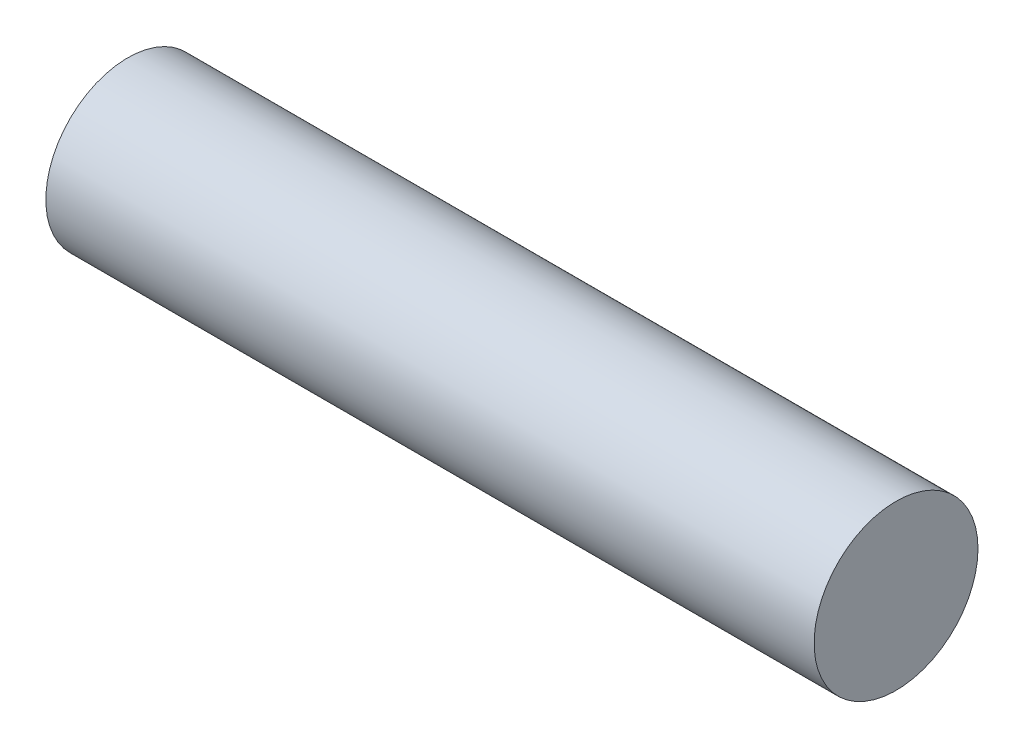
SolidWorks part; units mm, degrees
material "Brass"
ref_plane "Front Plane" through (0, 0, 0) normal (0, 0, 1) x (1, 0, 0)
ref_plane "Top Plane" through (0, 0, 0) normal (0, 1, 0) x (1, 0, 0)
ref_plane "Right Plane" through (0, 0, 0) normal (1, 0, 0) x (0, 0, -1)
sketch "Sketch1" plane through (0, 0, 0) normal (1, 0, 0) x (0, 0, -1)
  circle A0 centre (0, 0) radius 1.6
  dimension "D1" = 3.2
extrude "Boss-Extrude1" add sketch "Sketch1" along normal mid plane 15
